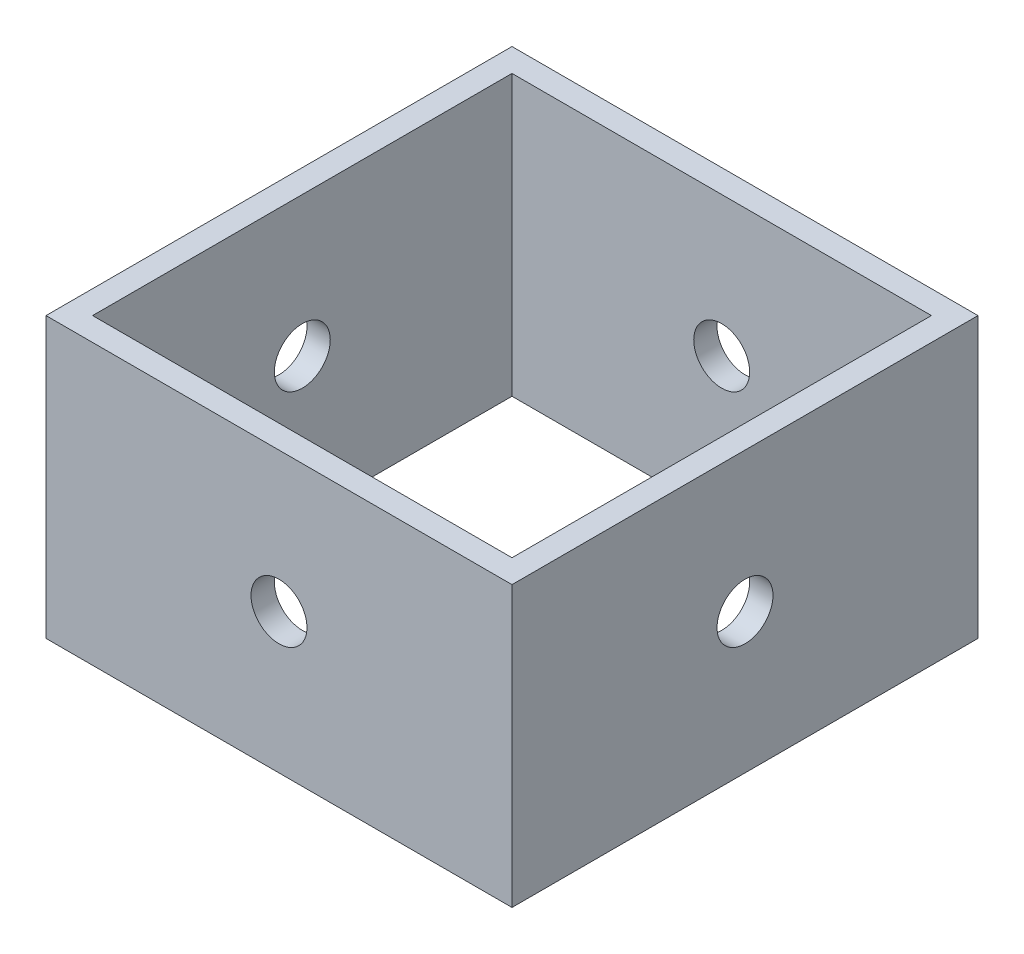
SolidWorks part; units mm, degrees
ref_plane "Front Plane" through (0, 0, 0) normal (0, 0, 1) x (1, 0, 0)
ref_plane "Top Plane" through (0, 0, 0) normal (0, 1, 0) x (1, 0, 0)
ref_plane "Right Plane" through (0, 0, 0) normal (1, 0, 0) x (0, 0, -1)
sketch "Sketch1" plane through (0, 0, 0) normal (0, 1, 0) x (1, 0, 0)
  line L1 (-12.5, 12.5) -> (12.5, 12.5)
  line L2 (-12.5, 12.5) -> (-12.5, -12.5)
  line L3 (-12.5, -12.5) -> (12.5, -12.5)
  line L4 (12.5, 12.5) -> (12.5, -12.5)
  line L5 (-12.5, 12.5) -> (12.5, -12.5) construction
  line L6 (-12.5, -12.5) -> (12.5, 12.5) construction
  line L7 (11.2504, 11.2504) -> (-11.2504, 11.2504)
  line L8 (11.2504, 11.2504) -> (11.2504, -11.2504)
  line L9 (11.2504, -11.2504) -> (-11.2504, -11.2504)
  line L10 (-11.2504, 11.2504) -> (-11.2504, -11.2504)
  line L11 (11.2504, 11.2504) -> (-11.2504, -11.2504) construction
  line L12 (11.2504, -11.2504) -> (-11.2504, 11.2504) construction
  point P0 (0, 0)
  point P6 (0, 0)
extrude "Boss-Extrude1" add sketch "Sketch1" along normal blind 15
sketch "Sketch2" plane through (0, 0, -12.5) normal (0, 0, -1) x (-1, 0, 0)
  line L0 (-12.5, 15) -> (42862.1463, -25709.7878) construction
  line L1 (12.5, 15) -> (-42862.1463, -25709.7878) construction
  circle A0 centre (0, 7.5) radius 1.5
extrude "Cut-Extrude1" cut sketch "Sketch2" against normal through all
sketch "Sketch3" plane through (12.5, 0, 0) normal (1, 0, 0) x (0, 0, -1)
  line L0 (-12.5, 15) -> (12.5, 0) construction
  line L2 (-12.5, 0) -> (12.5, 15) construction
  circle A0 centre (0, 7.5) radius 1.5
extrude "Cut-Extrude2" cut sketch "Sketch3" against normal through all
